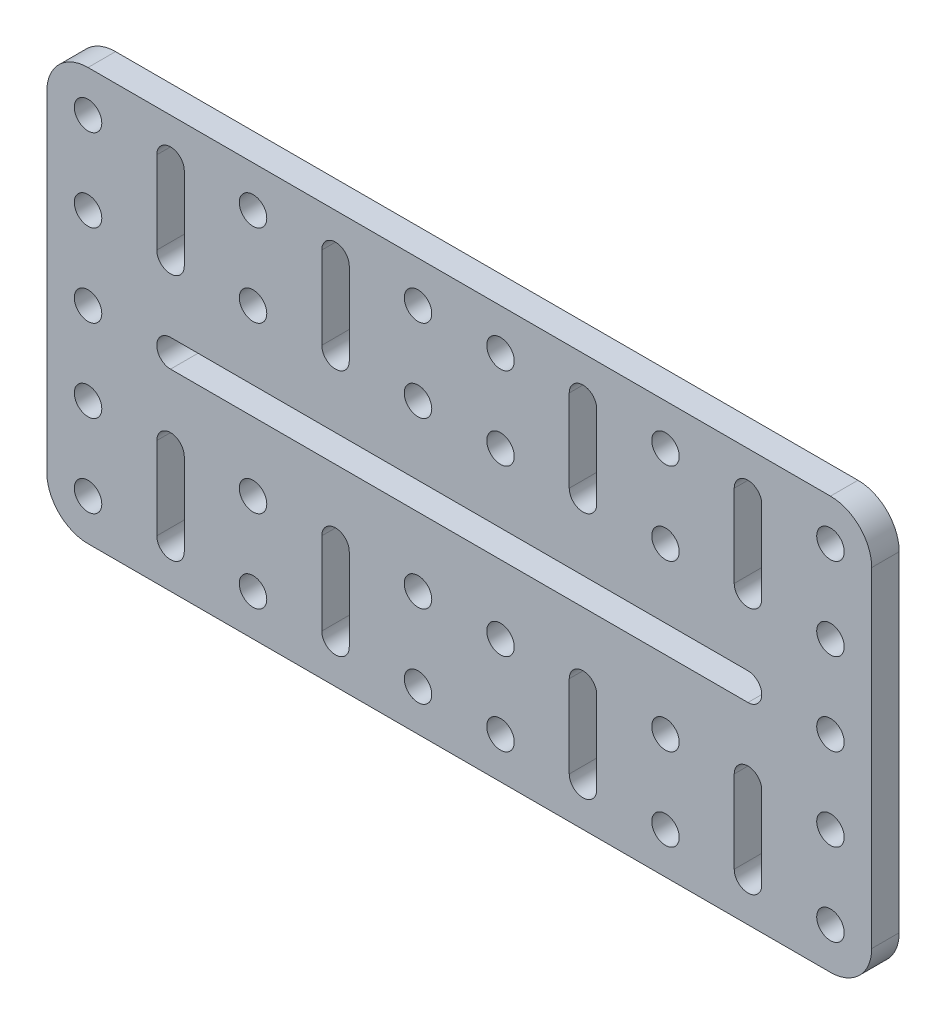
SolidWorks part; units mm, degrees
ref_plane "Alzado" through (0, 0, 0) normal (0, 0, 1) x (1, 0, 0)
ref_plane "Planta" through (0, 0, 0) normal (0, 1, 0) x (1, 0, 0)
ref_plane "Vista lateral" through (0, 0, 0) normal (1, 0, 0) x (0, 0, -1)
sketch "Model" plane through (0, 0, 0) normal (0, 0, 1) x (1, 0, 0)
  line L0 (-105.9434, 101.0565) -> (-105.9434, 65.0565)
  line L1 (-101.4434, 60.5565) -> (-20.4434, 60.5565)
  line L2 (-15.9434, 65.0565) -> (-15.9434, 101.0565)
  line L3 (-20.4434, 105.5565) -> (-101.4434, 105.5565)
  line L4 (-92.4434, 84.5565) -> (-29.4434, 84.5565)
  line L5 (-92.4434, 81.5565) -> (-29.4434, 81.5565)
  line L6 (-93.9434, 74.0565) -> (-93.9434, 65.0565)
  line L7 (-90.9434, 65.0565) -> (-90.9434, 74.0565)
  line L8 (-75.9434, 74.0565) -> (-75.9434, 65.0565)
  line L9 (-72.9434, 65.0565) -> (-72.9434, 74.0565)
  line L10 (-48.9434, 74.0565) -> (-48.9434, 65.0565)
  line L11 (-45.9434, 65.0565) -> (-45.9434, 74.0565)
  line L12 (-30.9434, 74.0565) -> (-30.9434, 65.0565)
  line L13 (-27.9434, 65.0565) -> (-27.9434, 74.0565)
  line L14 (-93.9434, 101.0565) -> (-93.9434, 92.0565)
  line L15 (-90.9434, 92.0565) -> (-90.9434, 101.0565)
  line L16 (-75.9434, 101.0565) -> (-75.9434, 92.0565)
  line L17 (-72.9434, 92.0565) -> (-72.9434, 101.0565)
  line L18 (-48.9434, 101.0565) -> (-48.9434, 92.0565)
  line L19 (-45.9434, 92.0565) -> (-45.9434, 101.0565)
  line L20 (-30.9434, 101.0565) -> (-30.9434, 92.0565)
  line L21 (-27.9434, 92.0565) -> (-27.9434, 101.0565)
  circle A0 centre (-101.4434, 101.0565) radius 1.5
  circle A1 centre (-83.4434, 101.0565) radius 1.5
  circle A2 centre (-65.4434, 101.0565) radius 1.5
  circle A3 centre (-56.4434, 101.0565) radius 1.5
  circle A4 centre (-38.4434, 101.0565) radius 1.5
  circle A5 centre (-101.4434, 92.0565) radius 1.5
  circle A6 centre (-83.4434, 92.0565) radius 1.5
  circle A7 centre (-65.4434, 92.0565) radius 1.5
  circle A8 centre (-56.4434, 92.0565) radius 1.5
  circle A9 centre (-38.4434, 92.0565) radius 1.5
  circle A10 centre (-101.4434, 83.0565) radius 1.5
  circle A11 centre (-101.4434, 65.0565) radius 1.5
  circle A12 centre (-83.4434, 65.0565) radius 1.5
  circle A13 centre (-65.4434, 65.0565) radius 1.5
  circle A14 centre (-56.4434, 65.0565) radius 1.5
  circle A15 centre (-38.4434, 65.0565) radius 1.5
  arc A16 (-101.4434, 105.5565) -> (-105.9434, 101.0565) centre (-101.4434, 101.0565) ccw
  arc A17 (-15.9434, 101.0565) -> (-20.4434, 105.5565) centre (-20.4434, 101.0565) ccw
  arc A18 (-105.9434, 65.0565) -> (-101.4434, 60.5565) centre (-101.4434, 65.0565) ccw
  arc A19 (-20.4434, 60.5565) -> (-15.9434, 65.0565) centre (-20.4434, 65.0565) ccw
  circle A20 centre (-20.4434, 101.0565) radius 1.5
  circle A21 centre (-20.4434, 92.0565) radius 1.5
  circle A22 centre (-20.4434, 83.0565) radius 1.5
  circle A23 centre (-20.4434, 65.0565) radius 1.5
  circle A24 centre (-101.4434, 74.0565) radius 1.5
  circle A25 centre (-83.4434, 74.0565) radius 1.5
  circle A26 centre (-65.4434, 74.0565) radius 1.5
  circle A27 centre (-56.4434, 74.0565) radius 1.5
  circle A28 centre (-38.4434, 74.0565) radius 1.5
  circle A29 centre (-20.4434, 74.0565) radius 1.5
  arc A30 (-92.4434, 84.5565) -> (-92.4434, 81.5565) centre (-92.4434, 83.0565) ccw
  arc A31 (-29.4434, 81.5565) -> (-29.4434, 84.5565) centre (-29.4434, 83.0565) ccw
  arc A32 (-90.9434, 74.0565) -> (-93.9434, 74.0565) centre (-92.4434, 74.0565) ccw
  arc A33 (-93.9434, 65.0565) -> (-90.9434, 65.0565) centre (-92.4434, 65.0565) ccw
  arc A34 (-75.9434, 65.0565) -> (-72.9434, 65.0565) centre (-74.4434, 65.0565) ccw
  arc A35 (-72.9434, 74.0565) -> (-75.9434, 74.0565) centre (-74.4434, 74.0565) ccw
  arc A36 (-45.9434, 74.0565) -> (-48.9434, 74.0565) centre (-47.4434, 74.0565) ccw
  arc A37 (-48.9434, 65.0565) -> (-45.9434, 65.0565) centre (-47.4434, 65.0565) ccw
  arc A38 (-27.9434, 74.0565) -> (-30.9434, 74.0565) centre (-29.4434, 74.0565) ccw
  arc A39 (-30.9434, 65.0565) -> (-27.9434, 65.0565) centre (-29.4434, 65.0565) ccw
  arc A40 (-90.9434, 101.0565) -> (-93.9434, 101.0565) centre (-92.4434, 101.0565) ccw
  arc A41 (-93.9434, 92.0565) -> (-90.9434, 92.0565) centre (-92.4434, 92.0565) ccw
  arc A42 (-75.9434, 92.0565) -> (-72.9434, 92.0565) centre (-74.4434, 92.0565) ccw
  arc A43 (-72.9434, 101.0565) -> (-75.9434, 101.0565) centre (-74.4434, 101.0565) ccw
  arc A44 (-45.9434, 101.0565) -> (-48.9434, 101.0565) centre (-47.4434, 101.0565) ccw
  arc A45 (-48.9434, 92.0565) -> (-45.9434, 92.0565) centre (-47.4434, 92.0565) ccw
  arc A46 (-27.9434, 101.0565) -> (-30.9434, 101.0565) centre (-29.4434, 101.0565) ccw
  arc A47 (-30.9434, 92.0565) -> (-27.9434, 92.0565) centre (-29.4434, 92.0565) ccw
extrude "Saliente-Extruir1" add sketch "Model" along normal blind 3
